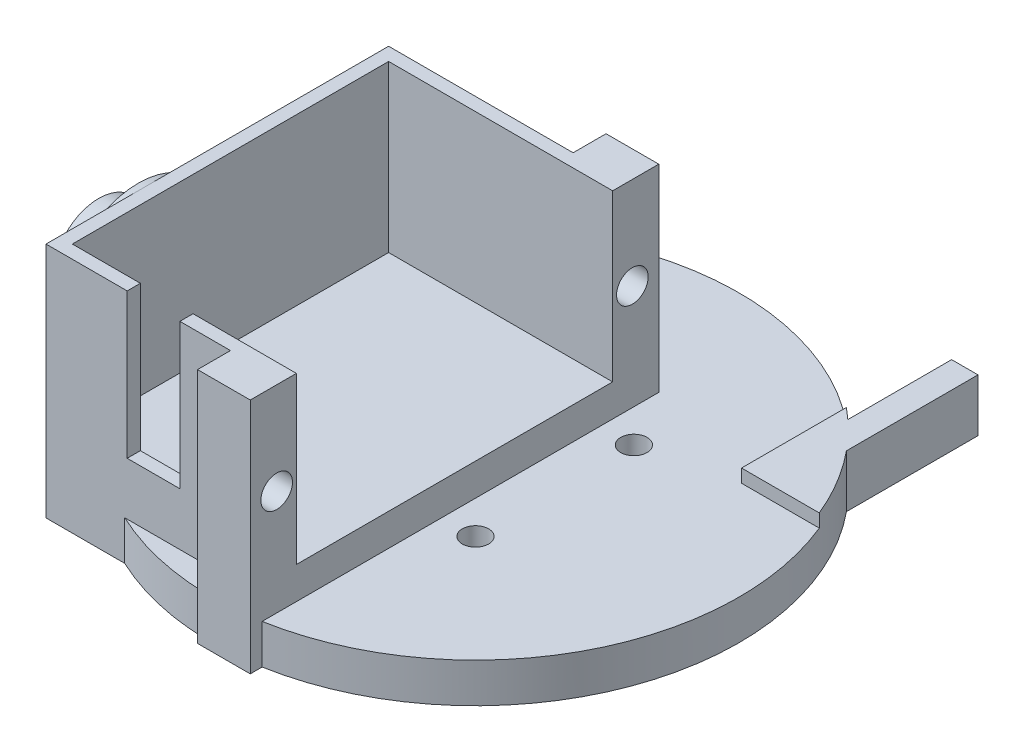
SolidWorks part; units mm, degrees
material "Plain Carbon Steel"
ref_plane "Front Plane" through (0, 0, 0) normal (0, 0, 1) x (1, 0, 0)
ref_plane "Top Plane" through (0, 0, 0) normal (0, 1, 0) x (1, 0, 0)
ref_plane "Right Plane" through (0, 0, 0) normal (1, 0, 0) x (0, 0, -1)
sketch "Sketch1" plane through (0, 0, 0) normal (0, 1, 0) x (1, 0, 0)
  circle A0 centre (0, 0) radius 100
  dimension "D1" = 200
extrude "Boss-Extrude1" add sketch "Sketch1" along normal blind 15
sketch "Sketch2" plane through (0, 15, 0) normal (0, 1, 0) x (1, 0, 0)
  line L0 (-2.5, 52.0432) -> (-2.5, 39.5432)
  line L1 (-2.5, 52.0432) -> (17.5, 52.0432)
  line L2 (-72.5, 39.5432) -> (-72.5, -90.4568)
  line L3 (-2.5, -102.9568) -> (17.5, -102.9568)
  line L4 (17.5, 52.0432) -> (17.5, -102.9568)
  line L5 (-2.5, 39.5432) -> (-72.5, 39.5432)
  line L6 (-2.5, -102.9568) -> (-2.5, -90.4568)
  line L7 (-2.5, -90.4568) -> (-72.5, -90.4568)
  circle A0 centre (0, 0) radius 100 construction
  point P4 (17.5, -98.4568)
  dimension "D1" = 12.5
  dimension "D2" = 72.5
  dimension "D3" = 155
  dimension "D4" = 4.5
  dimension "D5" = 20
  dimension "D6" = 12.5
  dimension "D7" = 90
extrude "Boss-Extrude2" add sketch "Sketch2" along normal blind 75 and the other way up to surface other way up to face at (0, 0, 100)
sketch "Sketch3" plane through (0, 90, 0) normal (0, 1, 0) x (1, 0, 0)
  line L0 (17.5, -102.9568) -> (17.5, 52.0432) construction
  line L5 (-67.5, 34.5432) -> (17.5, 34.5432)
  line L6 (-67.5, 34.5432) -> (-67.5, -85.4568)
  line L7 (-67.5, -85.4568) -> (17.5, -85.4568)
  line L8 (17.5, 34.5432) -> (17.5, -85.4568)
  line L9 (-72.5, -25.4568) -> (101.9146, -25.4568) construction
  line L10 (-72.5, 39.5432) -> (-72.5, -90.4568) construction
  line L11 (-72.5, 39.5432) -> (-72.5, -68.8749) construction
  line L12 (-2.5, 39.5432) -> (-72.5, 39.5432) construction
  dimension "D1" = 5
  dimension "D2" = 5
extrude "Cut-Extrude1" cut sketch "Sketch3" against normal blind 62.8
sketch "Sketch4" plane through (0, 0, 90.4568) normal (0, 0, 1) x (1, 0, 0)
  line L0 (-72.5, 90) -> (-2.5, 90) construction
  line L1 (-41.7, 90) -> (-21.7, 90)
  line L2 (-41.7, 90) -> (-41.7, 35)
  line L3 (-41.7, 35) -> (-21.7, 35)
  line L4 (-21.7, 90) -> (-21.7, 35)
  line L5 (-2.5, 15) -> (-2.5, 90) construction
  dimension "D1" = 19.2
  dimension "D2" = 55
  dimension "D3" = 20
extrude "Cut-Extrude2" cut sketch "Sketch4" against normal up to surface (5 mm away) up to face at (-25, 58.6, 85.4568)
sketch "Sketch5" plane through (-72.5, 0, 0) normal (-1, 0, 0) x (0, 0, 1)
  line L0 (-39.5432, 90) -> (90.4568, 90) construction
  line L1 (90.4568, 0) -> (90.4568, 90) construction
  circle A0 centre (52.9568, 60) radius 30
  dimension "D1" = 30
  dimension "D3" = 60
  dimension "D2" = 37.5
extrude "Boss-Extrude3" add sketch "Sketch5" along normal blind 2.5
sketch "Sketch6" plane through (-75, 0, 0) normal (-1, 0, 0) x (0, 0, 1)
  circle A0 centre (52.9568, 60) radius 17.5
  dimension "D1" = 35
extrude "Boss-Extrude4" add sketch "Sketch6" along normal blind 15
sketch "Sketch7" plane through (0, 15, 0) normal (0, 1, 0) x (1, 0, 0)
  line L0 (17.5, 34.5432) -> (93.8444, 34.5432) construction
  line L1 (63.0425, 37.8932) -> (92.5425, 37.8932)
  line L2 (63.0425, 37.8932) -> (63.0425, 77.625)
  line L3 (67.2925, 113.3711) -> (67.2925, 73.9711)
  line L4 (67.2925, 113.3711) -> (77.2925, 113.3711)
  line L5 (77.2925, 113.3711) -> (77.2925, 63.4498)
  arc A0 (17.5, -98.4568) -> (-72.5, -68.8749) centre (0, 0) ccw construction
  arc A1 (63.0425, 77.625) -> (67.2925, 73.9711) centre (0, 0) cw
  arc A2 (77.2925, 63.4498) -> (92.5425, 37.8932) centre (0, 0) cw
  dimension "D1" = 3.35
  dimension "D2" = 29.5
  dimension "D3" = 4.25
  dimension "D4" = 39.4
  dimension "D5" = 10
extrude "Boss-Extrude5" add sketch "Sketch7" along normal blind 5 and the other way up to surface other way up to face at (-14.2005, 0, 68.222)
sketch "Sketch8" plane through (17.5, 0, 0) normal (1, 0, 0) x (0, 0, -1)
  line L1 (-102.9568, 90) -> (-85.4568, 90) construction
  line L2 (-25.4568, 198.6448) -> (-25.4568, 27.2) construction
  line L3 (34.5432, 27.2) -> (-85.4568, 27.2) construction
  circle A0 centre (-92.9318, 55) radius 6
  circle A1 centre (42.0182, 55) radius 6
  dimension "D1" = 12
  dimension "D2" = 134.95
  dimension "D3" = 35
extrude "Cut-Extrude3" cut sketch "Sketch8" against normal up to surface (20 mm away) up to face at (-2.5, 35, 97.7941)
sketch "Sketch11" plane through (0, 0, 0) normal (0, -1, 0) x (1, 0, 0)
  line L0 (77.2925, -113.3711) -> (77.2925, -63.4498) construction
  line L5 (0, 72.1572) -> (0, -108.0628) construction
  line L6 (-30.052, 30.052) -> (30.052, 30.052) construction
  line L7 (-30.052, 30.052) -> (-30.052, -30.052) construction
  line L8 (-30.052, -30.052) -> (30.052, -30.052) construction
  line L9 (30.052, 30.052) -> (30.052, -30.052) construction
  line L10 (-30.052, 30.052) -> (30.052, -30.052) construction
  line L11 (-30.052, -30.052) -> (30.052, 30.052) construction
  circle A4 centre (-30.052, 30.052) radius 5
  circle A5 centre (30.052, 30.052) radius 5
  circle A6 centre (30.052, -30.052) radius 5
  circle A7 centre (-30.052, -30.052) radius 5
  point P0 (0, 0)
  dimension "D2" = 10
  dimension "D1" = 85
extrude "Cut-Extrude4" cut sketch "Sketch11" against normal up to surface (15 mm away) up to face at (7.5045, 15, -23.8728)
